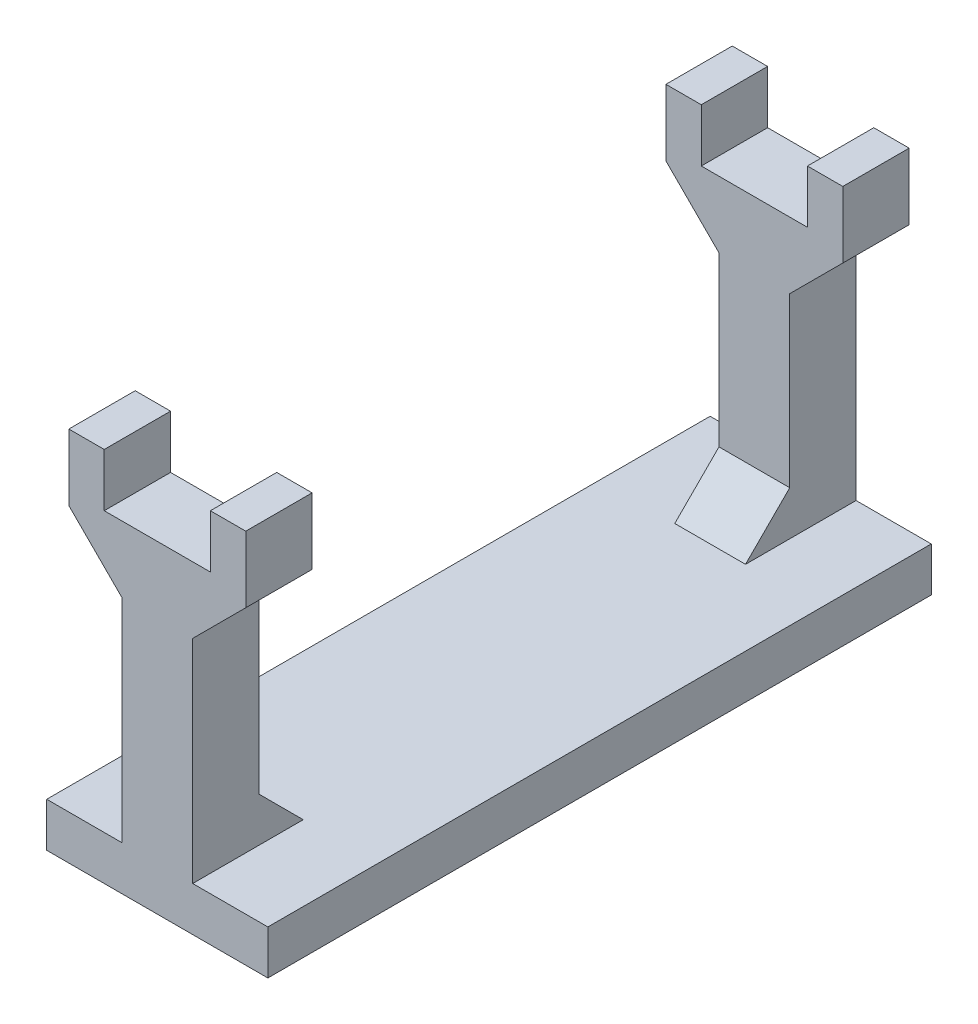
SolidWorks part; units mm, degrees
ref_plane "前视基准面" through (0, 0, 0) normal (0, 0, 1) x (1, 0, 0)
ref_plane "上视基准面" through (0, 0, 0) normal (0, 1, 0) x (1, 0, 0)
ref_plane "右视基准面" through (0, 0, 0) normal (1, 0, 0) x (0, 0, -1)
sketch "草图3" plane through (0, 0, 0) normal (0, 0, 1) x (1, 0, 0)
  line L0 (0, 0) -> (0, 10)
  line L1 (0, 10) -> (17, 10)
  line L2 (17, 10) -> (17, 58)
  line L4 (5, 70) -> (5, 85)
  line L5 (5, 85) -> (13, 85)
  line L6 (13, 85) -> (13, 73)
  line L7 (13, 73) -> (37, 73)
  line L8 (37, 73) -> (37, 85)
  line L9 (37, 85) -> (45, 85)
  line L10 (45, 85) -> (45, 70)
  line L12 (33, 58) -> (33, 10)
  line L13 (33, 10) -> (50, 10)
  line L14 (50, 10) -> (50, 0)
  line L15 (50, 0) -> (0, 0)
  line L16 (25, 73) -> (25, 0) construction
  line L17 (17, 58) -> (5, 70)
  line L18 (33, 58) -> (45, 70)
  dimension "D1" = 50
  dimension "D2" = 10
  dimension "D3" = 135
  dimension "D4" = 12
  dimension "D5" = 24
  dimension "D6" = 85
  dimension "D7" = 3
  dimension "D8" = 40
  dimension "D9" = 16
extrude "凸台-拉伸2" add sketch "草图3" along normal blind 150
sketch "草图4" plane through (50, 0, 0) normal (1, 0, 0) x (0, 0, -1)
  line L0 (-135, 85) -> (-135, 20)
  line L1 (-150, 85) -> (0, 85) construction
  line L2 (-150, 0) -> (0, 0) construction
  line L4 (-176.9656, 73) -> (-38.4807, 73) construction
  line L5 (-15, 20) -> (-15, 85)
  line L6 (-15, 85) -> (-135, 85)
  line L7 (-75, 10) -> (-75, 0) construction
  line L9 (-150, 70) -> (-150, 85) construction
  line L10 (-150, 73) -> (0, 73) construction
  line L15 (-135, 20) -> (-125, 10)
  line L18 (-15, 20) -> (-25, 10)
  line L24 (-125, 10) -> (-25, 10)
  line L25 (-150, 10) -> (0, 10) construction
  point P13 (-75, 0)
  dimension "D1" = 15
  dimension "D2" = 63
  dimension "D3" = 135
  dimension "D4" = 100
extrude "切除-拉伸2" cut sketch "草图4" against normal through all
